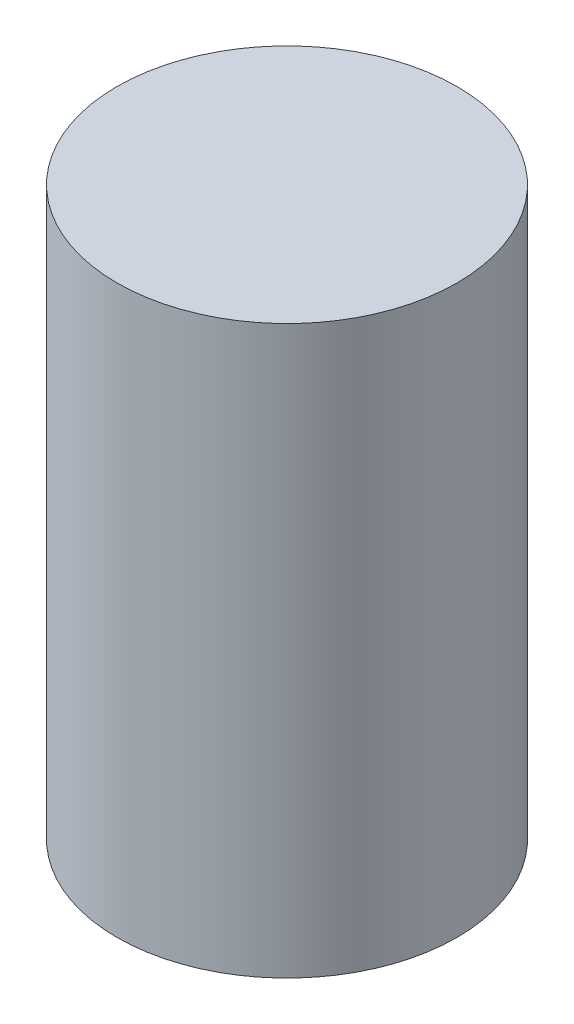
SolidWorks part; units mm, degrees
ref_plane "前视基准面" through (0, 0, 0) normal (0, 0, 1) x (1, 0, 0)
ref_plane "上视基准面" through (0, 0, 0) normal (0, 1, 0) x (1, 0, 0)
ref_plane "右视基准面" through (0, 0, 0) normal (1, 0, 0) x (0, 0, -1)
sketch "草图1" plane through (0, 0, 0) normal (0, 1, 0) x (1, 0, 0)
  circle A0 centre (0, 0) radius 3
  dimension "D1" = 6
extrude "凸台-拉伸1" add sketch "草图1" along normal blind 10
